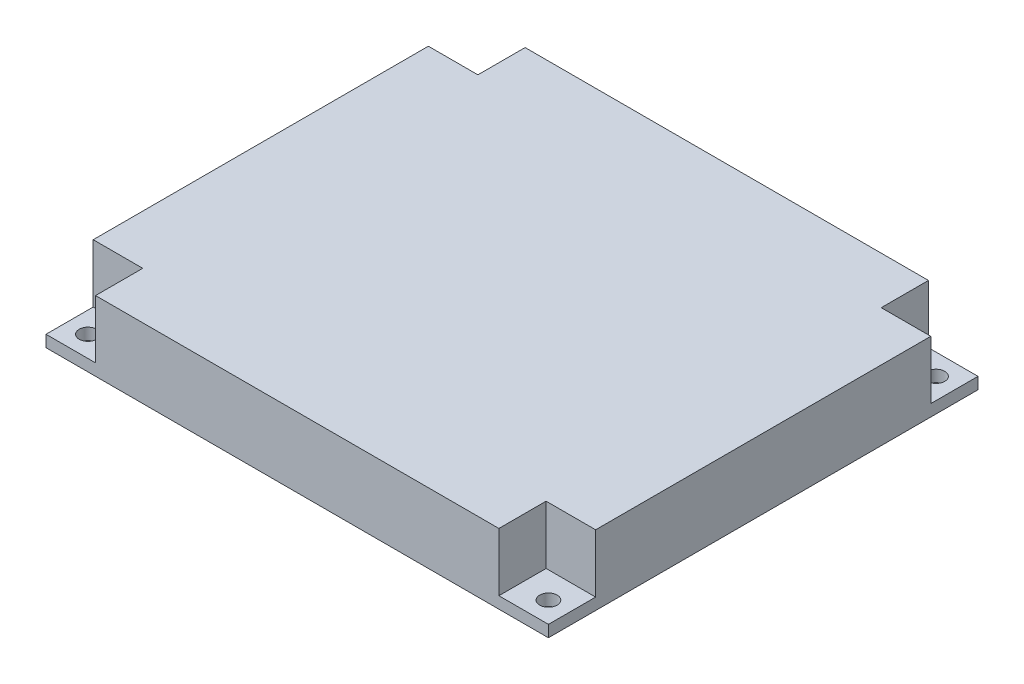
SolidWorks part; units mm, degrees
ref_plane "前视基准面" through (0, 0, 0) normal (0, 0, 1) x (1, 0, 0)
ref_plane "上视基准面" through (0, 0, 0) normal (0, 1, 0) x (1, 0, 0)
ref_plane "右视基准面" through (0, 0, 0) normal (1, 0, 0) x (0, 0, -1)
sketch "草图1" plane through (0, 0, 0) normal (0, 1, 0) x (1, 0, 0)
  line L1 (-43.1, 36.85) -> (43.1, 36.85)
  line L2 (-43.1, 36.85) -> (-43.1, -36.85)
  line L3 (-43.1, -36.85) -> (43.1, -36.85)
  line L4 (43.1, 36.85) -> (43.1, -36.85)
  line L5 (-43.1, 36.85) -> (43.1, -36.85) construction
  line L6 (-43.1, -36.85) -> (43.1, 36.85) construction
  circle A0 centre (-39.5, 33.25) radius 1.5
  circle A1 centre (39.5, 33.25) radius 1.5
  circle A2 centre (-39.5, -33.25) radius 1.5
  circle A3 centre (39.5, -33.25) radius 1.5
  point P0 (0, 0)
  point P16 (-39.8966, -33.1772)
  dimension "D3" = 3.6
  dimension "D1" = 73.7
  dimension "D2" = 86.2
  dimension "D4" = 3.6
  dimension "D5" = 3.6
  dimension "D6" = 3.6
  dimension "D7" = 66.5
  dimension "D8" = 79
extrude "凸台-拉伸1" add sketch "草图1" along normal blind 2
sketch "草图2" plane through (0, 2, 0) normal (0, 1, 0) x (1, 0, 0)
  line L0 (-43.1, -36.85) -> (43.1, -36.85) construction
  line L1 (-34.6, 36.85) -> (34.6, 36.85)
  line L2 (-34.6, 36.85) -> (-34.6, 28.75)
  line L3 (-34.6, -36.85) -> (34.6, -36.85)
  line L4 (34.6, 36.85) -> (34.6, 28.75)
  line L7 (43.1, -36.85) -> (43.1, 36.85) construction
  line L8 (-43.1, 28.75) -> (-34.6, 28.75)
  line L9 (-43.1, 28.75) -> (-43.1, -28.75)
  line L10 (-43.1, -28.75) -> (-34.6, -28.75)
  line L11 (43.1, 28.75) -> (43.1, -28.75)
  line L12 (34.6, -28.75) -> (34.6, -36.85)
  line L14 (43.1, 36.85) -> (-43.1, 36.85) construction
  line L15 (34.6, 28.75) -> (43.1, 28.75)
  line L18 (-34.6, -28.75) -> (-34.6, -36.85)
  line L19 (34.6, -28.75) -> (43.1, -28.75)
  point P0 (0, 0)
  point P8 (0, 0)
  dimension "D1" = 8.1
  dimension "D2" = 8.5
extrude "凸台-拉伸2" add sketch "草图2" along normal blind 10
